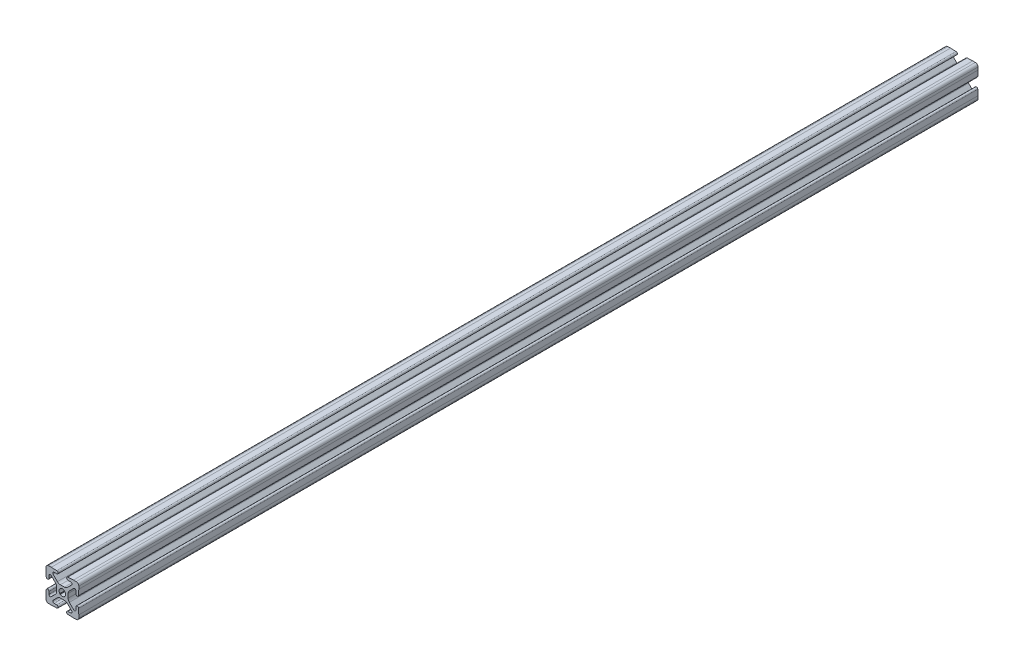
SolidWorks part; units mm, degrees
ref_plane "Front Plane" through (0, 0, 0) normal (0, 0, 1) x (1, 0, 0)
ref_plane "Top Plane" through (0, 0, 0) normal (0, 1, 0) x (1, 0, 0)
ref_plane "Right Plane" through (0, 0, 0) normal (1, 0, 0) x (0, 0, -1)
sketch "Model" plane through (0, 0, 0) normal (0, 0, 1) x (1, 0, 0)
  line L38 (50.6495, 75.4336) -> (50.2699, 75.4336)
  line L39 (50.2699, 75.4336) -> (50.2699, 75.8133)
  line L40 (50.66, 72.9999) -> (53.7746, 72.9999)
  line L41 (56.0196, 72.0699) -> (59.2642, 68.8254)
  line L42 (58.5103, 67.0916) -> (56.5725, 67.1592)
  line L43 (56.498, 65.0269) -> (60.6773, 64.881)
  line L44 (60.6773, 64.881) -> (62.7107, 64.881)
  line L45 (64.7173, 66.8876) -> (64.7173, 68.921)
  line L46 (64.7173, 68.921) -> (64.5713, 73.1002)
  line L47 (62.439, 73.0257) -> (62.5067, 71.0879)
  line L48 (60.7729, 70.334) -> (57.5283, 73.5786)
  line L49 (56.5984, 75.8237) -> (56.5984, 78.9383)
  line L50 (57.5283, 81.1833) -> (60.7729, 84.4279)
  line L51 (62.5067, 83.674) -> (62.439, 81.7362)
  line L52 (64.5713, 81.6617) -> (64.7173, 85.841)
  line L53 (64.7173, 85.841) -> (64.7173, 87.8744)
  line L54 (62.7107, 89.881) -> (60.6773, 89.881)
  line L55 (60.6773, 89.881) -> (56.498, 89.735)
  line L56 (56.5725, 87.6027) -> (58.5103, 87.6704)
  line L57 (59.2642, 85.9366) -> (56.0196, 82.692)
  line L58 (53.7746, 81.7621) -> (50.66, 81.7621)
  line L59 (48.4149, 82.692) -> (45.1703, 85.9366)
  line L60 (45.9242, 87.6704) -> (47.862, 87.6027)
  line L61 (47.9365, 89.735) -> (43.7573, 89.881)
  line L62 (43.7573, 89.881) -> (41.7239, 89.881)
  line L63 (39.7173, 87.8744) -> (39.7173, 85.841)
  line L64 (39.7173, 85.841) -> (39.8632, 81.6617)
  line L65 (41.9955, 81.7362) -> (41.9278, 83.674)
  line L66 (43.6616, 84.4279) -> (46.9062, 81.1833)
  line L67 (47.8361, 78.9383) -> (47.8361, 75.8237)
  line L68 (46.9062, 73.5786) -> (43.6616, 70.334)
  line L69 (41.9278, 71.0879) -> (41.9955, 73.0257)
  line L70 (39.8632, 73.1002) -> (39.7173, 68.921)
  line L71 (39.7173, 68.921) -> (39.7173, 66.8876)
  line L72 (41.7239, 64.881) -> (43.7573, 64.881)
  line L73 (43.7573, 64.881) -> (47.9365, 65.0269)
  line L74 (47.862, 67.1592) -> (45.9242, 67.0916)
  line L75 (45.1703, 68.8254) -> (48.4149, 72.0699)
  arc A29 (50.6495, 75.4336) -> (50.2699, 75.8133) centre (52.2173, 77.381) ccw
  arc A30 (56.0196, 72.0699) -> (53.7746, 72.9999) centre (53.7746, 69.8249) ccw
  arc A31 (58.5103, 67.0916) -> (59.2642, 68.8254) centre (58.5458, 68.1069) ccw
  arc A32 (56.5725, 67.1592) -> (56.498, 65.0269) centre (56.5353, 66.0931) ccw
  arc A33 (62.7107, 64.881) -> (64.7173, 66.8876) centre (62.7107, 66.8876) ccw
  arc A34 (64.5713, 73.1002) -> (62.439, 73.0257) centre (63.5052, 73.063) ccw
  arc A35 (60.7729, 70.334) -> (62.5067, 71.0879) centre (61.4913, 71.0525) ccw
  arc A36 (56.5984, 75.8237) -> (57.5283, 73.5786) centre (59.7734, 75.8237) ccw
  arc A37 (57.5283, 81.1833) -> (56.5984, 78.9383) centre (59.7734, 78.9383) ccw
  arc A38 (62.5067, 83.674) -> (60.7729, 84.4279) centre (61.4913, 83.7095) ccw
  arc A39 (62.439, 81.7362) -> (64.5713, 81.6617) centre (63.5052, 81.699) ccw
  arc A40 (64.7173, 87.8744) -> (62.7107, 89.881) centre (62.7107, 87.8744) ccw
  arc A41 (56.498, 89.735) -> (56.5725, 87.6027) centre (56.5353, 88.6689) ccw
  arc A42 (59.2642, 85.9366) -> (58.5103, 87.6704) centre (58.5458, 86.655) ccw
  arc A43 (53.7746, 81.7621) -> (56.0196, 82.692) centre (53.7746, 84.9371) ccw
  arc A44 (48.4149, 82.692) -> (50.66, 81.7621) centre (50.66, 84.9371) ccw
  arc A45 (45.9242, 87.6704) -> (45.1703, 85.9366) centre (45.8887, 86.655) ccw
  arc A46 (47.862, 87.6027) -> (47.9365, 89.735) centre (47.8993, 88.6689) ccw
  arc A47 (41.7239, 89.881) -> (39.7173, 87.8744) centre (41.7239, 87.8744) ccw
  arc A48 (39.8632, 81.6617) -> (41.9955, 81.7362) centre (40.9293, 81.699) ccw
  arc A49 (43.6616, 84.4279) -> (41.9278, 83.674) centre (42.9432, 83.7095) ccw
  arc A50 (47.8361, 78.9383) -> (46.9062, 81.1833) centre (44.6611, 78.9383) ccw
  arc A51 (46.9062, 73.5786) -> (47.8361, 75.8237) centre (44.6611, 75.8237) ccw
  arc A52 (41.9278, 71.0879) -> (43.6616, 70.334) centre (42.9432, 71.0525) ccw
  arc A53 (41.9955, 73.0257) -> (39.8632, 73.1002) centre (40.9293, 73.063) ccw
  arc A54 (39.7173, 66.8876) -> (41.7239, 64.881) centre (41.7239, 66.8876) ccw
  arc A55 (47.9365, 65.0269) -> (47.862, 67.1592) centre (47.8993, 66.0931) ccw
  arc A56 (45.1703, 68.8254) -> (45.9242, 67.0916) centre (45.8887, 68.1069) ccw
  arc A57 (50.66, 72.9999) -> (48.4149, 72.0699) centre (50.66, 69.8249) ccw
extrude "Boss-Extrude1" add sketch "Model" along normal blind 685.8
